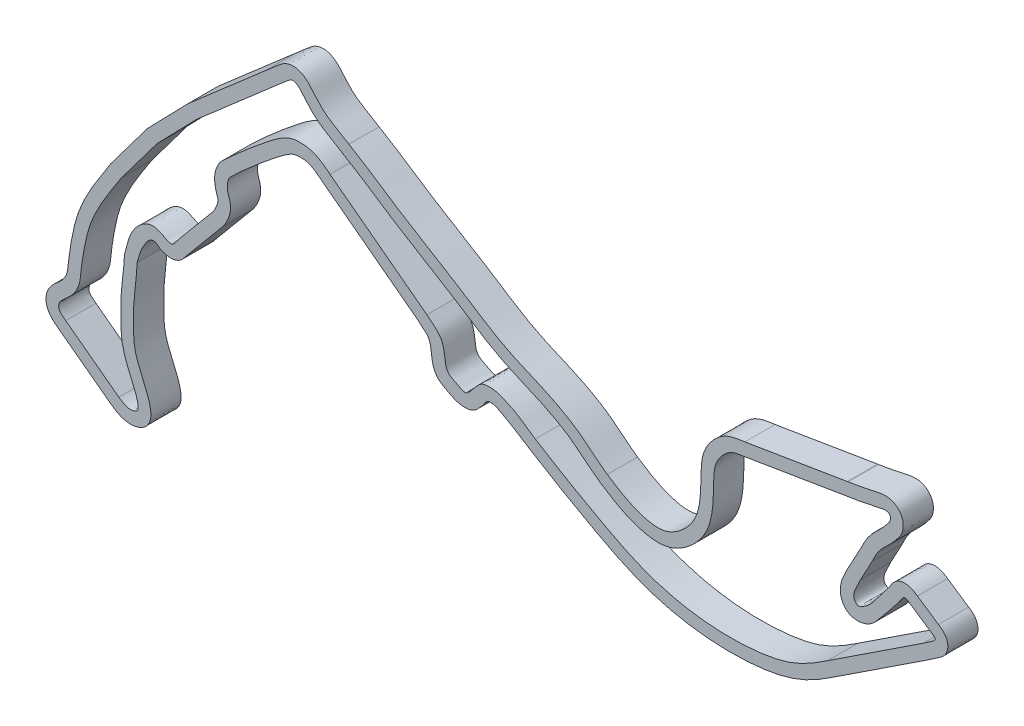
SolidWorks part; units mm, degrees
ref_plane "Front Plane" through (0, 0, 0) normal (0, 0, 1) x (1, 0, 0)
ref_plane "Top Plane" through (0, 0, 0) normal (0, 1, 0) x (1, 0, 0)
ref_plane "Right Plane" through (0, 0, 0) normal (1, 0, 0) x (0, 0, -1)
sketch "Sketch1" plane through (0, 0, 0) normal (0, 0, 1) x (1, 0, 0)
  line L0 (106.0112, 138.7783) -> (530.0561, 138.7783) construction
  line L1 (276.4176, 102.2318) -> (242.4299, 96.6097)
  line L2 (284.0268, 87.7249) -> (280.0602, 80.3037)
  line L3 (289.6588, 83.1024) -> (284.58, 76.467)
  line L4 (296.5825, 81.6526) -> (303.7425, 76.8564)
  line L5 (85.7013, 124.6871) -> (60.2065, 102.5198)
  line L6 (60.2065, 102.5198) -> (47.0646, 88.9811)
  line L7 (47.0646, 88.9811) -> (35.1906, 73.1627)
  line L8 (0, 0) -> (25.5394, 16.5215) construction
  line L9 (34.4036, 9.894) -> (16.8101, 23.0482)
  line L10 (82.8678, 127.789) -> (57.3166, 105.5727)
  line L11 (57.3166, 105.5727) -> (43.8655, 91.7154)
  line L12 (43.8655, 91.7154) -> (31.7317, 75.551)
  line L13 (31.8886, 6.5302) -> (14.2538, 19.7154)
  line L15 (34.4036, 9.894) -> (31.8886, 6.5302)
  line L16 (275.7322, 106.3755) -> (241.7955, 100.7619)
  line L17 (110.6402, 120.5632) -> (108.4322, 116.9881)
  line L18 (275.7322, 106.3755) -> (276.4176, 102.2318)
  line L19 (276.0437, 106.4151) -> (275.7322, 106.3755)
  line L20 (280.2209, 89.5012) -> (284.0268, 87.7249)
  line L21 (269.2136, 51.7057) -> (300.9102, 72.5695)
  line L22 (298.9488, 85.1227) -> (305.9273, 80.4482)
  line L23 (271.5462, 48.2129) -> (303.1883, 69.0408)
  line L24 (289.6588, 83.1024) -> (293.1385, 80.7504)
  line L26 (65.2112, 78.2712) -> (54.7635, 65.7641)
  line L27 (104.3712, 108.7975) -> (136.4435, 84.5792)
  line L28 (31.8886, 6.5302) -> (31.9169, 6.5092)
  line L29 (40.4564, 51.5422) -> (36.2596, 51.7057)
  line L30 (57.3166, 62.2692) -> (54.7635, 65.7641)
  line L31 (271.5462, 48.2129) -> (269.2136, 51.7057)
  line L32 (271.5228, 48.1975) -> (303.1883, 69.0408) construction
  line L33 (172.3633, 66.8588) -> (170.1572, 63.2849)
  line L34 (68.4246, 75.5667) -> (57.3166, 62.2692)
  line L35 (68.4345, 75.5786) -> (57.9868, 63.0715) construction
  line L36 (101.8403, 105.4457) -> (133.9125, 81.2275)
  line L37 (68.9014, 76.1375) -> (68.4246, 75.5667)
  line L38 (101.6052, 105.6369) -> (101.8403, 105.4457)
  line L39 (133.9125, 81.2275) -> (136.4435, 84.5792)
  spline S0 degree 3 poles (85.7013, 124.6871) (86.9816, 125.9208) (88.8653, 127.2771) (92.2183, 130.5429) (94.9397, 127.8298) (96.9546, 125.2854) (100.9953, 121.0055) (105.5235, 118.9174) (108.4322, 116.9881) knots 0 0 0 0 0.172513 0.280369 0.402846 0.48805 0.636271 1 1 1 1
  spline S1 degree 3 poles (16.8101, 23.0482) (15.9647, 23.7133) (14.2025, 24.8309) (14.6189, 27.3803) (16.4073, 29.1808) (18.702, 31.0062) (20.5174, 33.6506) (21.6485, 36.7573) (21.9425, 41.5996) (22.9473, 46.9795) (25.3746, 58.665) (31.1109, 66.7229) (35.1906, 73.1627) knots 0 0 0 0 0.060723 0.088781 0.124345 0.192969 0.244851 0.29234 0.366969 0.50094 0.583564 1 1 1 1
  spline S2 degree 1 poles (82.8678, 127.789) (110.7537, 120.4882) knots 0 0 1 1 construction
  spline S3 degree 1 poles (14.2538, 19.7154) (31.7317, 75.551) knots 0 0 1 1 construction
  spline S4 degree 3 poles (110.7537, 120.4882) (110.2079, 120.8503) (109.0755, 121.5587) (107.4783, 122.4961) (105.9579, 123.3848) (104.5546, 124.2485) (103.2757, 125.1244) (102.1675, 126.0084) (101.0951, 127.0355) (100.2175, 127.9973) (99.5552, 128.7836) (98.9907, 129.4702) (98.3358, 130.2431) (97.5297, 131.1381) (96.6214, 132.0023) (95.6724, 132.6979) (94.7952, 133.1998) (93.6879, 133.6241) (92.5319, 133.8091) (91.511, 133.7603) (90.5962, 133.5949) (89.6424, 133.2476) (88.7702, 132.7631) (87.8591, 132.1222) (87.0246, 131.3873) (86.4073, 130.8307) (85.7769, 130.2998) (85.1213, 129.7594) (84.4186, 129.1775) (83.6751, 128.5395) (83.128, 128.0377) (82.8678, 127.789) knots 0.003077 0.003077 0.003077 0.003077 0.065385 0.127693 0.19 0.252308 0.314616 0.376923 0.439231 0.501539 0.532692 0.563846 0.595 0.626154 0.657308 0.672885 0.688462 0.704039 0.719615 0.727404 0.735192 0.750769 0.766346 0.781923 0.813077 0.844231 0.875385 0.906538 0.937692 0.968846 1 1 1 1 only from (110.6402, 120.5632) to (82.8678, 127.789)
  spline S5 degree 3 poles (31.7317, 75.551) (31.4274, 75.0706) (30.82, 74.1186) (29.5601, 72.1659) (27.9434, 69.6588) (26.0018, 66.5257) (24.1342, 63.2552) (22.4164, 59.8283) (21.1789, 56.8248) (20.3477, 54.3264) (19.6458, 51.7563) (19.0303, 48.742) (18.4565, 45.7901) (18.0581, 43.3235) (17.803, 41.4281) (17.6288, 39.5288) (17.46, 38.0135) (17.2138, 36.8834) (16.8096, 35.8281) (16.3474, 35.0269) (15.8944, 34.4193) (15.537, 34.0095) (15.0795, 33.5533) (14.5212, 33.0433) (13.8587, 32.4595) (13.1558, 31.8276) (12.2514, 30.9717) (11.2998, 29.7634) (10.6755, 28.4186) (10.3725, 27.3466) (10.2337, 26.1778) (10.3225, 24.8533) (10.7494, 23.4989) (11.3357, 22.4733) (11.9629, 21.6781) (12.5668, 21.0695) (13.1196, 20.591) (13.5992, 20.2141) (13.9981, 19.9136) (14.1606, 19.7887) (14.2538, 19.7154) knots -0.000972 -0.000972 -0.000972 -0.000972 0.030403 0.061778 0.124528 0.187279 0.250029 0.312779 0.375529 0.406904 0.438279 0.501029 0.563779 0.595155 0.62653 0.657905 0.68928 0.720655 0.75203 0.783405 0.799093 0.81478 0.830468 0.846155 0.861843 0.87753 0.893218 0.908905 0.916749 0.924593 0.932437 0.94028 0.948124 0.955968 0.963812 0.971655 0.979499 0.987343 0.995187 1.003031 1.003031 1.003031 1.003031
  spline S6 degree 3 poles (108.4322, 116.9881) (114.127, 113.7118) (125.4569, 105.6234) (143.6072, 95.3813) (159.4348, 84.2281) (173.4914, 78.9856) (184.9596, 72.7646) (189.4464, 68.2556) (193.8585, 65.1668) knots 0 0 0 0 0.19677 0.41605 0.625495 0.770642 0.869433 1 1 1 1
  spline S7 degree 3 poles (193.8585, 65.1668) (197.9689, 62.4049) (204.6228, 58.4169) (216.2239, 56.7408) (224.5855, 61.849) (230.2474, 69.677) (231.3616, 77.6041) (231.4446, 84.6224) (231.6641, 90.3184) (236.4799, 95.7513) (239.1664, 96.1524) (242.4299, 96.6097) knots 0 0 0 0 0.196171 0.307152 0.445248 0.559693 0.68215 0.754046 0.833198 0.914439 1 1 1 1
  spline S8 degree 1 poles (110.5267, 120.6286) (196.2345, 68.6303) knots 0 0 1 1 construction
  spline S9 degree 1 poles (196.2345, 68.6303) (241.7955, 100.7619) knots 0 0 1 1 construction
  spline S10 degree 3 poles (110.5267, 120.6286) (111.4637, 120.0895) (113.3278, 118.9781) (116.9491, 116.7007) (121.3508, 113.7823) (126.5005, 110.3456) (133.415, 106.0246) (140.6041, 101.8068) (147.8413, 97.2599) (153.0954, 93.797) (157.4046, 91.077) (160.8548, 89.0879) (163.4386, 87.7198) (166.0864, 86.4688) (169.7834, 84.8478) (174.6351, 82.8186) (179.735, 80.367) (183.6289, 78.1386) (186.4119, 76.3099) (188.8603, 74.4228) (190.7515, 72.8628) (192.2994, 71.6012) (193.5088, 70.6408) (194.5874, 69.8189) (195.5034, 69.148) (195.9922, 68.8002) (196.2345, 68.6303) knots 0 0 0 0 0.031239 0.062479 0.124957 0.187436 0.249914 0.374871 0.43735 0.499828 0.562307 0.593546 0.624785 0.656024 0.687264 0.749742 0.812221 0.84346 0.874699 0.905938 0.937178 0.952797 0.968417 0.984037 0.991846 0.999656 0.999656 0.999656 0.999656 only from (110.6402, 120.5632) to (196.2345, 68.6303)
  spline S11 degree 3 poles (196.2345, 68.6303) (196.8632, 68.2082) (198.1371, 67.3682) (200.6525, 65.8059) (203.8029, 64.0899) (207.6455, 62.552) (210.952, 61.7958) (213.3573, 61.6938) (214.9478, 61.8687) (216.5331, 62.3348) (218.7002, 63.3473) (221.3687, 65.3054) (223.5906, 67.7691) (224.927, 69.8755) (225.701, 71.5006) (226.2769, 73.2632) (226.8366, 75.8631) (227.1051, 78.7461) (227.2092, 81.8018) (227.2479, 83.7667) (227.2857, 85.3797) (227.3701, 87.1552) (227.6186, 89.1405) (228.2682, 91.2899) (229.2666, 93.4471) (230.8754, 95.7081) (232.7532, 97.5456) (234.4091, 98.7285) (235.8029, 99.4582) (237.244, 99.9587) (238.656, 100.2827) (239.8738, 100.4852) (240.9239, 100.6394) (241.51, 100.7219) (241.7955, 100.7619) knots 0.000552 0.000552 0.000552 0.000552 0.031771 0.062989 0.125427 0.187864 0.250302 0.28152 0.312739 0.343958 0.375177 0.437614 0.500052 0.53127 0.562489 0.593708 0.624926 0.687364 0.718583 0.749801 0.765411 0.78102 0.812239 0.827848 0.843458 0.874676 0.905895 0.921504 0.937114 0.952723 0.968332 0.983942 0.991747 0.999551 0.999551 0.999551 0.999551
  spline S12 degree 3 poles (276.4176, 102.2318) (278.4821, 102.4163) (281.6656, 103.2834) (285.4842, 103.8598) (287.5089, 104.4093) (288.9628, 104.4549) (290.0056, 103.8207) (290.1318, 102.2647) (289.4136, 101.3157) (288.3555, 99.9803) (286.6539, 98.0725) (284.3833, 96.1251) (282.0386, 93.2231) (280.8231, 90.7914) (280.2209, 89.5012) knots 0 0 0 0 0.198526 0.317824 0.368633 0.403434 0.429131 0.458812 0.509949 0.556035 0.64271 0.745984 0.846317 1 1 1 1
  spline S13 degree 1 poles (276.0437, 106.4151) (284.0268, 87.7249) knots 0 0 1 1 construction
  spline S14 degree 3 poles (276.0437, 106.4151) (276.2992, 106.4379) (276.7977, 106.4963) (277.8784, 106.6696) (279.3351, 106.9729) (280.9653, 107.3376) (282.3778, 107.6085) (283.3509, 107.7809) (284.1048, 107.9193) (284.6673, 108.0322) (285.067, 108.1185) (285.4505, 108.2104) (286.0253, 108.349) (286.7699, 108.494) (287.6168, 108.6063) (288.8909, 108.6464) (290.3293, 108.3748) (291.5713, 107.7947) (292.3856, 107.2053) (293.0094, 106.5493) (293.4496, 105.9341) (293.7739, 105.3022) (294.0603, 104.5217) (294.2274, 103.6554) (294.2616, 102.7682) (294.1945, 101.9764) (293.98, 100.9437) (293.4979, 99.8196) (292.9993, 99.0981) (292.7328, 98.7498) (292.5548, 98.5213) (292.302, 98.1993) (291.9934, 97.8158) (291.5526, 97.2826) (290.9578, 96.5944) (290.1877, 95.7573) (289.345, 94.9159) (288.5805, 94.2044) (287.911, 93.5795) (287.3712, 93.0444) (286.8825, 92.5018) (286.2552, 91.7246) (285.5506, 90.6866) (284.7396, 89.2195) (284.2607, 88.2261) (284.0268, 87.7249) knots 0 0 0 0 0.03125 0.0625 0.125 0.1875 0.21875 0.25 0.28125 0.296875 0.3125 0.328125 0.34375 0.359375 0.375 0.390625 0.40625 0.414062 0.421875 0.425781 0.429688 0.433594 0.4375 0.445312 0.453125 0.460938 0.46875 0.484375 0.5 0.507812 0.515625 0.53125 0.546875 0.5625 0.59375 0.625 0.65625 0.6875 0.71875 0.75 0.78125 0.8125 0.875 0.9375 1 1 1 1
  spline S15 degree 3 poles (280.0602, 80.3037) (279.477, 78.9725) (278.3078, 77.0815) (277.5272, 74.1074) (279.1744, 72.0877) (282.0927, 73.7309) (283.5866, 75.1113) (284.58, 76.467) knots 0 0 0 0 0.279248 0.444097 0.560672 0.683148 1 1 1 1
  spline S16 degree 3 poles (296.5825, 81.6526) (296.1148, 81.9762) (294.5558, 83.1324) (293.6979, 81.5291) (293.4163, 81.1615) (293.1385, 80.7504) knots 0 0 0 0 0.534492 0.76027 1 1 1 1
  spline S17 degree 3 poles (303.7425, 76.8564) (303.957, 76.7492) (304.5854, 76.2876) (304.9948, 75.6064) (304.2357, 74.8166) (302.8836, 74.0117) (301.7485, 73.0986) (300.9102, 72.5695) knots 0 0 0 0 0.119035 0.260232 0.372326 0.544277 1 1 1 1
  spline S18 degree 1 poles (298.9488, 85.1227) (289.6588, 83.1024) knots 0 0 1 1 construction
  spline S19 degree 1 poles (305.9273, 80.4482) (303.1883, 69.0408) knots 0 0 1 1 construction
  spline S20 degree 3 poles (289.6588, 83.1024) (289.7307, 83.2087) (289.8931, 83.4449) (290.0364, 83.6504) (290.0982, 83.742) (290.132, 83.7952) (290.1543, 83.8302) (290.3062, 84.0915) (290.6954, 84.6859) (291.312, 85.4087) (292.2296, 86.0766) (293.3969, 86.608) (294.731, 86.7787) (295.9263, 86.6188) (296.7973, 86.3432) (297.6861, 85.9431) (298.3119, 85.5581) (298.6969, 85.2982) (298.8679, 85.1793) (298.919, 85.1435) (298.9488, 85.1227) knots 0.012213 0.012213 0.012213 0.012213 0.073949 0.135686 0.197423 0.228291 0.259159 0.320896 0.382633 0.44437 0.475238 0.506106 0.567843 0.62958 0.691316 0.753053 0.876527 0.938263 0.969132 1 1 1 1
  spline S21 degree 3 poles (305.9273, 80.4482) (306.0932, 80.3526) (306.426, 80.1398) (306.9821, 79.7185) (307.5252, 79.2413) (308.1913, 78.4156) (308.718, 77.4834) (309.0266, 76.3154) (309.0211, 75.2283) (308.8607, 74.389) (308.5902, 73.6871) (308.2068, 72.9934) (307.7539, 72.4196) (307.3071, 71.9728) (306.8456, 71.5729) (306.3201, 71.1853) (305.846, 70.8811) (305.6145, 70.7322) (305.2656, 70.4935) (304.7546, 70.1257) (304.0504, 69.6144) (303.4712, 69.2204) (303.1883, 69.0408) knots 0.015886 0.015886 0.015886 0.015886 0.046486 0.077085 0.138283 0.168883 0.199482 0.230081 0.245381 0.26068 0.27598 0.29128 0.321879 0.352478 0.383077 0.444276 0.505474 0.566673 0.627871 0.750268 0.872665 0.995062 0.995062 0.995062 0.995062
  spline S22 degree 3 poles (280.2209, 89.5012) (278.6746, 86.7425) (277.3759, 84.1948) (275.5699, 81.132) (273.7082, 76.8758) (273.4013, 74.5482) (273.3513, 72.5445) (274.9781, 68.94) (278.9402, 67.7699) (283.7958, 68.9105) (287.0392, 73.1975) (290.3711, 77.1224) (292.2664, 79.6173) (293.1385, 80.7504) knots 0 0 0 0 0.174467 0.265327 0.299348 0.342412 0.404118 0.48045 0.567366 0.655825 0.794314 0.9053 1 1 1 1
  spline S23 degree 3 poles (136.4435, 84.5792) (137.9438, 83.3097) (140.7795, 81.3181) (142.1002, 77.7418) (142.4524, 74.3423) (143.0068, 71.4274) (145.968, 69.8696) (146.4106, 69.6686) (149.3399, 68.183) (151.5609, 70.595) (152.4227, 71.6128) (153.8191, 73.4833) (155.7478, 74.2078) (158.5245, 74.2774) (160.5421, 73.6472) (166.5946, 71.2851) (169.3794, 68.6999) (172.3633, 66.8588) knots 0 0 0 0 0.127325 0.186002 0.257062 0.315269 0.365632 0.421647 0.444492 0.468791 0.521672 0.589822 0.615464 0.648895 0.69859 0.793174 1 1 1 1
  spline S24 degree 3 poles (104.3712, 108.7975) (102.8363, 110.1408) (99.4051, 112.571) (95.0966, 113.139) (90.8363, 112.8305) (85.8736, 109.6693) (82.4906, 106.824) (78.7229, 103.9066) (73.3458, 99.0657) (73.6462, 99.4802) (68.4705, 94.7283) (67.3185, 93.3851) (66.0834, 90.2307) (66.1143, 87.0148) (66.662, 84.7905) (67.567, 82.5967) (66.1153, 79.3993) (65.5806, 78.6699) (65.2112, 78.2712) knots 0 0 0 0 0.104552 0.186643 0.247573 0.305959 0.401526 0.505855 0.603404 0.69541 0.731087 0.768287 0.802741 0.839402 0.884975 0.926689 0.959178 1 1 1 1
  spline S25 degree 3 poles (34.4036, 9.894) (35.7208, 8.9262) (37.8876, 7.69) (40.9828, 9.0712) (40.736, 11.4471) (40.0122, 13.9458) (38.4055, 17.5789) (36.4057, 22.1411) (35.0816, 27.411) (35.0422, 34.4418) (35.0618, 41.3685) (36.0869, 47.2709) (36.2596, 51.7057) knots 0 0 0 0 0.099784 0.135404 0.172334 0.224242 0.296982 0.406911 0.519479 0.632547 0.765853 1 1 1 1
  spline S26 degree 3 poles (57.3166, 62.2692) (56.8118, 61.5928) (55.6266, 60.0777) (54.3677, 58.9986) (51.8452, 58.1412) (48.7398, 58.8119) (47.7732, 59.59) (46.1108, 60.7962) (44.1884, 59.9623) (42.6015, 57.4487) (41.515, 55.3658) (41.5281, 55.0896) (40.4564, 51.5422) knots 0 0 0 0 0.113185 0.204196 0.294311 0.385663 0.482413 0.552192 0.610711 0.674629 0.786453 1 1 1 1
  spline S27 degree 1 poles (31.9169, 6.5092) (40.4564, 51.5422) knots 0 0 1 1 construction
  spline S28 degree 3 poles (31.9169, 6.5092) (32.1854, 6.312) (32.7068, 5.9442) (33.9892, 5.1558) (35.5754, 4.4406) (37.5657, 4.0684) (39.2277, 4.0861) (40.6363, 4.3879) (41.88, 4.9089) (42.8859, 5.5359) (43.7497, 6.3645) (44.363, 7.3153) (44.7841, 8.2755) (45.0109, 9.3528) (45.0464, 10.7195) (44.9017, 11.6348) (44.777, 12.3138) (44.6267, 13.0056) (44.413, 13.8164) (44.1232, 14.7273) (43.8161, 15.5785) (43.3851, 16.6759) (42.827, 17.9725) (42.187, 19.4151) (41.5807, 20.8141) (40.8408, 22.6173) (40.1023, 24.724) (39.6288, 26.7983) (39.4051, 28.604) (39.273, 30.6549) (39.2526, 32.8809) (39.2495, 34.988) (39.2586, 36.9012) (39.315, 39.054) (39.5353, 41.6404) (39.8793, 44.5906) (40.1762, 47.3175) (40.3639, 49.663) (40.4323, 50.9226) (40.4564, 51.5422) knots 0 0 0 0 0.015625 0.03125 0.0625 0.078125 0.09375 0.109375 0.117188 0.125 0.132812 0.136719 0.140625 0.148438 0.15625 0.171875 0.179688 0.1875 0.203125 0.21875 0.234375 0.25 0.28125 0.3125 0.34375 0.375 0.4375 0.5 0.53125 0.5625 0.625 0.65625 0.6875 0.75 0.8125 0.875 0.9375 0.96875 1 1 1 1
  spline S29 degree 3 poles (36.2596, 51.7057) (36.9103, 54.2439) (37.7525, 58.5942) (41.2041, 63.0134) (45.1869, 65.185) (48.5857, 64.0071) (51.9241, 61.8977) (53.1541, 63.7033) (54.3522, 65.2097) (54.7635, 65.7641) knots 0 0 0 0 0.285199 0.458661 0.594042 0.732518 0.84268 0.937289 1 1 1 1
  spline S30 degree 3 poles (269.2136, 51.7057) (265.3523, 49.0891) (258.2031, 44.7185) (246.6367, 42.5317) (234.8375, 41.932) (221.9842, 43.1543) (208.3014, 46.9098) (191.8895, 55.1211) (180.0692, 62.1021) (172.3633, 66.8588) knots 0 0 0 0 0.134956 0.235936 0.334653 0.474283 0.604979 0.739944 1 1 1 1
  spline S31 degree 1 poles (271.5697, 48.2288) (170.1572, 63.2849) knots 0 0 1 1 construction
  spline S32 degree 3 poles (271.5697, 48.2288) (270.6361, 47.5961) (268.7726, 46.3629) (264.8069, 43.9527) (260.5372, 41.8083) (255.8929, 40.2443) (251.2419, 39.1249) (245.4921, 38.3277) (238.6454, 37.9318) (231.7952, 38.0771) (224.9615, 38.7472) (218.1896, 39.9576) (211.5232, 41.7175) (205.006, 44.0864) (198.8276, 46.9532) (192.9278, 50.0371) (187.1384, 53.2116) (179.5088, 57.5849) (173.8878, 60.982) (170.1572, 63.2849) knots 0 0 0 0 0.03125 0.0625 0.125 0.15625 0.1875 0.25 0.3125 0.375 0.4375 0.5 0.5625 0.625 0.6875 0.75 0.8125 0.875 1 1 1 1 only from (271.5462, 48.2129) to (170.1572, 63.2849)
  spline S33 degree 1 poles (101.6052, 105.6369) (68.2921, 75.4168) knots 0 0 1 1 construction
  spline S34 degree 3 poles (101.6052, 105.6369) (101.2097, 105.9831) (100.3971, 106.6453) (99.0832, 107.552) (97.8345, 108.2237) (96.8714, 108.5679) (96.0134, 108.729) (95.2048, 108.7951) (94.4879, 108.813) (93.7852, 108.7981) (93.1841, 108.7404) (92.6265, 108.6292) (92.1352, 108.4742) (91.4629, 108.1667) (90.3956, 107.5636) (88.9451, 106.5829) (87.533, 105.5388) (85.902, 104.2326) (84.2589, 102.899) (82.6291, 101.5955) (81.3425, 100.5339) (79.8795, 99.272) (78.3987, 97.9662) (77.1848, 96.8901) (76.4038, 96.2314) (76.1331, 96.0143) (75.5797, 95.5297) (74.9146, 94.9329) (73.8715, 93.9846) (72.6131, 92.8227) (71.5301, 91.7877) (71.1547, 91.357) (71.0841, 91.2569) (70.7336, 90.5575) (70.4521, 89.7088) (70.3435, 89.0914) (70.3161, 88.3479) (70.3772, 87.5665) (70.4738, 86.9699) (70.5854, 86.5245) (70.7043, 86.1382) (70.8594, 85.6824) (71.1763, 84.7696) (71.3966, 83.4536) (71.4288, 82.3073) (71.2443, 81.0484) (70.9456, 80.0473) (70.6133, 79.1834) (70.1564, 78.1864) (69.6673, 77.2606) (69.1147, 76.401) (68.6289, 75.79) (68.4094, 75.5433) (68.2921, 75.4168) knots 0 0 0 0 0.03125 0.0625 0.09375 0.125 0.15625 0.171875 0.1875 0.203125 0.21875 0.234375 0.25 0.265625 0.28125 0.3125 0.34375 0.375 0.4375 0.46875 0.5 0.53125 0.5625 0.59375 0.625 0.65625 0.671875 0.6875 0.703125 0.71875 0.734375 0.75 0.765625 0.78125 0.796875 0.8125 0.828125 0.84375 0.859375 0.875 0.882812 0.890625 0.90625 0.914062 0.921875 0.929688 0.9375 0.945312 0.953125 0.96875 0.984375 0.992188 1 1 1 1 only from (101.6052, 105.6369) to (68.9014, 76.1375)
  spline S35 degree 3 poles (170.1572, 63.2849) (167.3801, 64.9527) (166.3728, 65.841) (160.7193, 69.0262) (158.7465, 69.9693) (156.2658, 69.9878) (155.2672, 68.0708) (154.4372, 67.2463) (153.3048, 65.9662) (151.7451, 64.5663) (148.5188, 64.0878) (145.6685, 64.7701) (143.6803, 65.8827) (139.6529, 67.9177) (138.2194, 71.6666) (137.9174, 74.6796) (137.4285, 78.8058) (134.769, 80.2547) (133.9125, 81.2275) knots 0 0 0 0 0.12345 0.236003 0.282672 0.306034 0.348776 0.38967 0.423045 0.463832 0.501053 0.565769 0.642012 0.720225 0.77214 0.834228 0.919452 1 1 1 1
  dimension "D1" = 4.2
  dimension "D2" = 4.2
  dimension "D3" = 4.2
  dimension "D4" = 4.2
  dimension "D5" = 4.2
  dimension "D6" = 4.2
  dimension "D7" = 4.2
  dimension "D8" = 4.2
  dimension "D9" = 4.2
extrude "Boss-Extrude1" add sketch "Sketch1" along normal blind 10 contours S11 S10 L17 S6 S7 L1 L18 L16 | S14 L19 L18 S12 L20 | L20 S22 L24 L3 S15 L2 | S21 L22 S20 L24 S16 L4 S17 L21 L31 L23 | S32 L31 S30 L33 | S35 L33 S23 L39 | S34 L38 L36 L39 L27 S24 L26 L30 L34 L37 | S29 L29 S26 L30 | L12 S5 L13 L15 L9 S1 L7 L6 L5 S0 L17 S4 L10 L11 | L28 S28 L29 S25 L15
ref_plane "Plane1" through (11.602, 15.5174, 0) normal (-0.5988, -0.8009, 0) x (-0.8009, 0.5988, 0)
